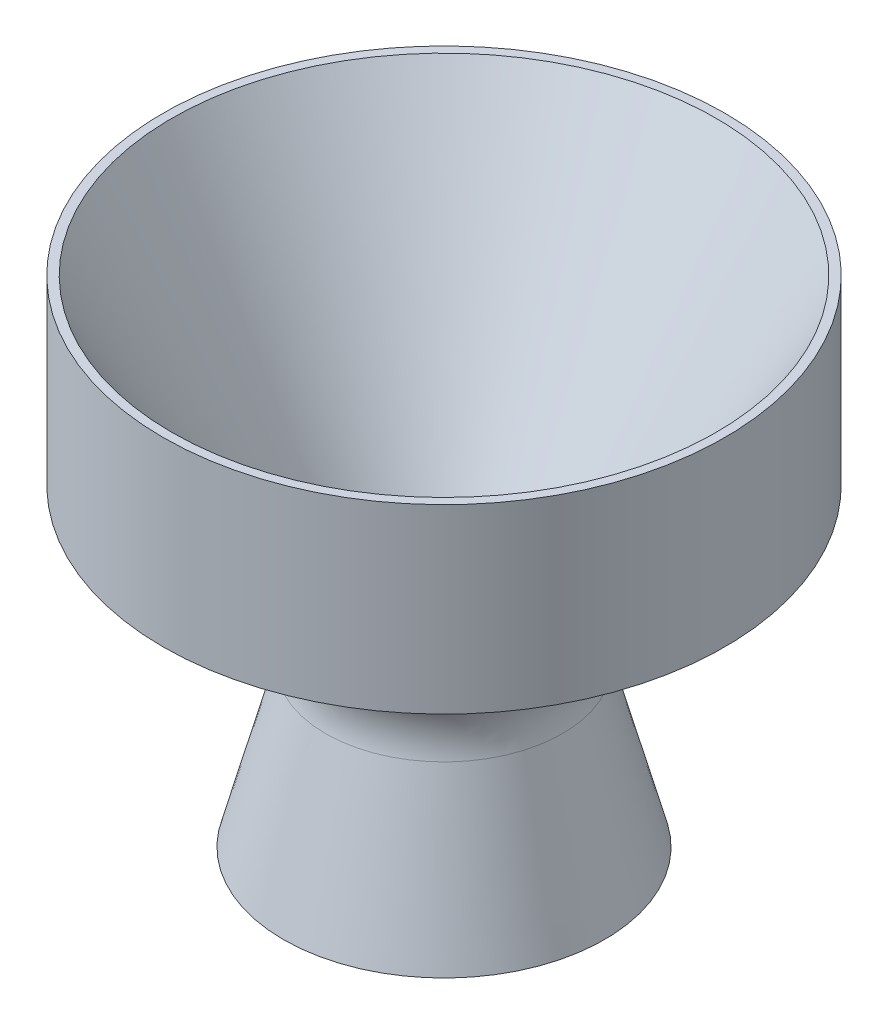
SolidWorks part; units mm, degrees
material "6061-T6 (SS)"
ref_plane "Front Plane" through (0, 0, 0) normal (0, 0, 1) x (1, 0, 0)
ref_plane "Top Plane" through (0, 0, 0) normal (0, 1, 0) x (1, 0, 0)
ref_plane "Right Plane" through (0, 0, 0) normal (1, 0, 0) x (0, 0, -1)
sketch "Sketch1" plane through (0, 0, 0) normal (0, 0, 1) x (1, 0, 0)
  line L0 (0, 0) -> (0, -61517.8545) construction
  line L1 (37.5, 42.2573) -> (13.2858, 0.317)
  line L3 (20.0594, -25.9627) -> (22.13, -25.9627)
  line L4 (22.13, -25.9627) -> (15.249, -0.2826)
  line L6 (15.249, -0.2826) -> (25.3756, 17.2573)
  line L7 (25.3756, 17.2573) -> (38.71, 17.2573)
  line L11 (38.71, 42.2573) -> (37.5, 42.2573)
  line L12 (38.71, 42.2573) -> (38.71, 17.2573)
  line L13 (13.2858, -0.683) -> (20.0594, -25.9627)
  line L14 (13.2858, 0.317) -> (13.2858, -0.683)
  line L15 (13.2858, 0.317) -> (13.1028, 0) construction
  line L16 (13.1028, 0) -> (13.2858, -0.683) construction
  dimension "D4" = 77.42
  dimension "D10" = 1
  dimension "D1" = 2
  dimension "D2" = 15
  dimension "D3" = 68.22
  dimension "D5" = 44.26
  dimension "D6" = 25
  dimension "D7" = 30
  dimension "D8" = 2
  dimension "D9" = 75
revolve "Revolve1" add sketch "Sketch1" angle 360 about L0
fillet "Fillet1" radius 10 2 edges at (0, 17.2573, 25.3756) (0, -0.2826, 15.249)
